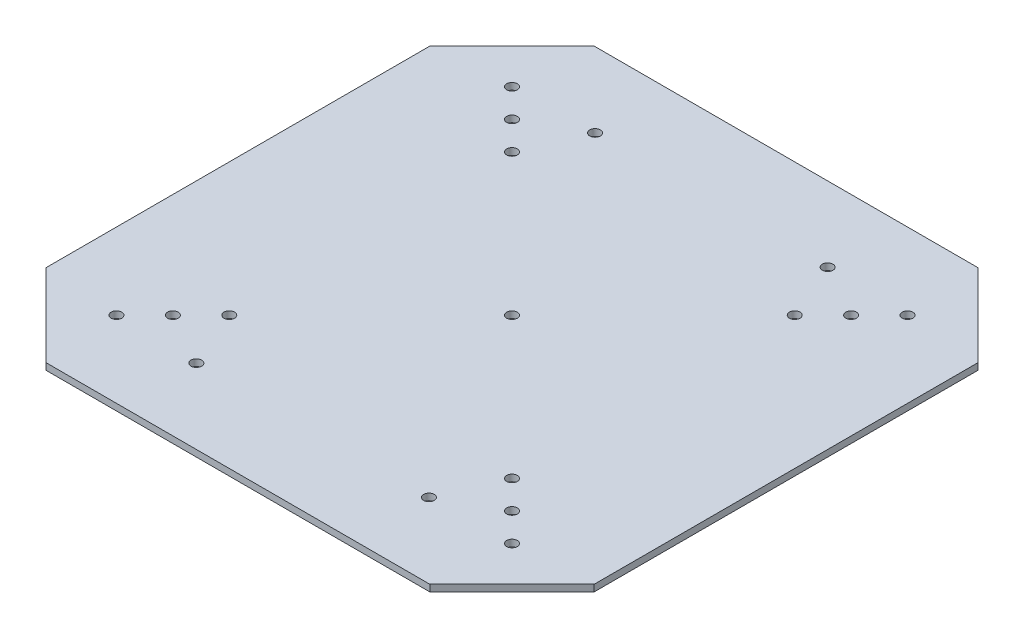
SolidWorks part; units mm, degrees
material "Thornel Mat VMA"
ref_plane "Front Plane" through (0, 0, 0) normal (0, 0, 1) x (1, 0, 0)
ref_plane "Top Plane" through (0, 0, 0) normal (0, 1, 0) x (1, 0, 0)
ref_plane "Right Plane" through (0, 0, 0) normal (1, 0, 0) x (0, 0, -1)
sketch "Sketch1" plane through (0, 0, 0) normal (0, 1, 0) x (1, 0, 0)
  line L0 (-57.7513, 82.5) -> (-82.5, 57.7513)
  line L1 (-57.7513, 82.5) -> (57.7513, 82.5)
  line L2 (-82.5, 57.7513) -> (-82.5, -57.7513)
  line L3 (-57.7513, -82.5) -> (57.7513, -82.5)
  line L4 (82.5, 57.7513) -> (82.5, -57.7513)
  line L5 (-70.1256, 70.1256) -> (70.1256, -70.1256) construction
  line L6 (-70.1256, -70.1256) -> (70.1256, 70.1256) construction
  line L7 (82.5, -57.7513) -> (57.7513, -82.5)
  line L8 (57.7513, 82.5) -> (82.5, 57.7513)
  line L9 (-82.5, -57.7513) -> (-57.7513, -82.5)
  point P0 (0, 0)
  point P9 (-70.1256, 70.1256)
  point P12 (70.1256, -70.1256)
  point P16 (70.1256, 70.1256)
  point P18 (-70.1256, -70.1256)
  dimension "D1" = 165
  dimension "D2" = 35
  dimension "D3" = 35
  dimension "D4" = 35
  dimension "D5" = 35
  dimension "D6" = 165
extrude "Boss-Extrude1" add sketch "Sketch1" along normal blind 2
hole_wizard "M3 Clearance Hole1" positions "Sketch4" profile "Sketch5" hole size "M3" standard "ANSI Metric" end condition through all
sketch "Sketch4" plane through (0, 0, 0) normal (0, -1, 0) x (-1, 0, 0)
  line L2 (70.1256, -70.1256) -> (-70.1256, 70.1256) construction
  line L3 (82.5, -57.7513) -> (57.7513, -82.5) construction
  line L4 (-82.5, 57.7513) -> (-57.7513, 82.5) construction
  line L6 (70.1256, 70.1256) -> (-70.1256, -70.1256) construction
  line L7 (57.7513, 82.5) -> (82.5, 57.7513) construction
  line L8 (-57.7513, -82.5) -> (-82.5, -57.7513) construction
  point P26 (59.519, 59.519)
  point P28 (51.0337, 51.0337)
  point P30 (42.5485, 42.5485)
  point P32 (-59.519, -59.519)
  point P34 (-51.0337, -51.0337)
  point P36 (-42.5485, -42.5485)
  point P38 (-59.519, 59.519)
  point P40 (-51.0337, 51.0337)
  point P42 (-42.5485, 42.5485)
  point P44 (59.519, -59.519)
  point P46 (51.0337, -51.0337)
  point P48 (42.5485, -42.5485)
  point P51 (0, 0)
  point P52 (50.2727, 50.2727)
  point P53 (49.0214, 49.0214)
  dimension "D1" = 15
  dimension "D2" = 12
  dimension "D3" = 12
  dimension "D4" = 12
  dimension "D5" = 12
  dimension "D6" = 15
  dimension "D7" = 12
  dimension "D8" = 12
  dimension "D9" = 15
  dimension "D10" = 12
  dimension "D11" = 12
  dimension "D12" = 15
sketch "Sketch5" plane through (-42.5485, 0, 42.5485) normal (1, 0, 0) x (0, 0, -1)
  line L0 (0, 0) -> (0, 2)
  line L1 (0, 2) -> (1.6, 2)
  line L2 (1.6, 2) -> (1.6, 0)
  line L5 (1.6, 0) -> (0, 0)
  line L11 (0, -6.35) -> (0, 107.95) construction
  dimension "Thru Hole Dia." = 3.2
  dimension "Thru Hole Depth" = 2
hole_wizard "M3 Clearance Hole2" positions "Sketch6" profile "Sketch7" hole size "M3" standard "ANSI Metric" end condition through all
sketch "Sketch6" plane through (0, 2, 0) normal (0, 1, 0) x (1, 0, 0)
  line L1 (35, -60) -> (-35, -60)
  line L2 (35, -60) -> (35, 60)
  line L3 (35, 60) -> (-35, 60)
  line L4 (-35, -60) -> (-35, 60)
  line L5 (35, -60) -> (-35, 60) construction
  line L6 (35, 60) -> (-35, -60) construction
  point P1 (0, 0)
  point P2 (-35, 60)
  point P77 (35, -60)
  point P78 (35, 60)
  point P79 (-35, -60)
  dimension "D1" = 70
  dimension "D2" = 120
sketch "Sketch7" plane through (0, 2, 0) normal (1, 0, 0) x (0, 0, 1)
  line L0 (0, 0) -> (0, 2)
  line L1 (0, 2) -> (1.6, 2)
  line L2 (1.6, 2) -> (1.6, 0)
  line L5 (1.6, 0) -> (0, 0)
  line L11 (0, -6.35) -> (0, 107.95) construction
  dimension "Thru Hole Dia." = 3.2
  dimension "Thru Hole Depth" = 2
